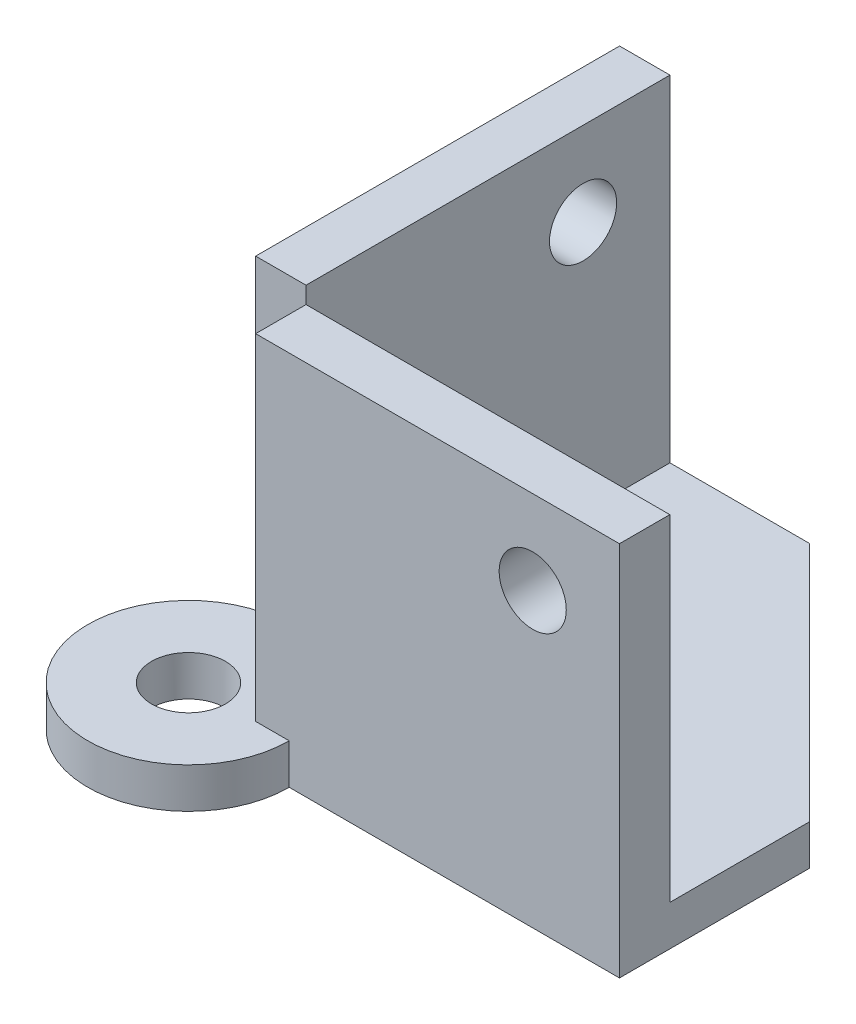
SolidWorks part; units mm, degrees
ref_plane "前视" through (0, 0, 0) normal (0, 0, 1) x (1, 0, 0)
ref_plane "上视" through (0, 0, 0) normal (0, 1, 0) x (1, 0, 0)
ref_plane "右视" through (0, 0, 0) normal (1, 0, 0) x (0, 0, -1)
sketch "Sketch1" plane through (0, 0, 0) normal (0, 1, 0) x (1, 0, 0)
  line L0 (0, 0) -> (0, 19)
  line L1 (0, 0) -> (19, 0)
  line L2 (19, 0) -> (0, 19)
  dimension "D1" = 19
  dimension "D2" = 19
extrude "Boss-Extrude1" add sketch "Sketch1" along normal blind 5
sketch "Sketch2" plane through (0, 5, 0) normal (0, 1, 0) x (1, 0, 0)
  line L0 (0, 19) -> (0, 0)
  line L1 (0, 0) -> (19, 0)
  line L2 (19, 0) -> (16, 3)
  line L3 (19, 0) -> (0, 19) construction
  line L4 (16, 3) -> (3, 3)
  line L5 (3, 3) -> (3, 16)
  line L6 (3, 16) -> (0, 19)
  dimension "D1" = 3
  dimension "D2" = 3
extrude "Boss-Extrude2" add sketch "Sketch2" along normal blind 15
sketch "Sketch3" plane through (0, 0, 0) normal (0, 0, 1) x (1, 0, 0)
  line L0 (0, 20) -> (0, 0) construction
  line L1 (0, 0) -> (19, 0) construction
  circle A0 centre (11.5, 15) radius 2
  dimension "D1" = 11.5
  dimension "D2" = 15
extrude "Cut-Extrude1" cut sketch "Sketch3" against normal through all
sketch "Sketch4" plane through (0, 0, 0) normal (-1, 0, 0) x (0, 0, 1)
  line L0 (-19, 0) -> (0, 0) construction
  line L1 (0, 20) -> (0, 0) construction
  circle A0 centre (-11.5, 15) radius 2
  dimension "D1" = 15
  dimension "D2" = 11.5
extrude "Cut-Extrude2" cut sketch "Sketch4" against normal through all
fillet "Fillet1" radius 1 6 edges at (9.5, 20, -3) (3, 20, -9.5) (1.5, 20, -17.5) (17.5, 20, -1.5) (19, 10, 0) (0, 10, -19)
sketch "Sketch5" plane through (0, 0, 0) normal (0, -1, 0) x (1, 0, 0)
  line L0 (28, 9) -> (-9, 9)
  line L1 (-9, 9) -> (-9, -28)
  line L3 (1.7071, -17.2929) -> (17.2929, -1.7071)
  line L4 (16.5858, 0) -> (0, 0)
  line L5 (0, 0) -> (0, -16.5858)
  line L6 (-9, -28) -> (28, 9)
  line L7 (0, 0) -> (16.5858, 0) construction
  line L8 (0, -16.5858) -> (0, 0) construction
  arc A2 (17.2929, -1.7071) -> (16.5858, 0) centre (16.5858, -1) ccw
  arc A3 (0, -16.5858) -> (1.7071, -17.2929) centre (1, -16.5858) ccw
  dimension "D2" = 9
  dimension "D3" = 9
  dimension "D1" = 0
extrude "Boss-Extrude3" add sketch "Sketch5" along normal blind 2.4
sketch "Sketch6" plane through (0, 0, 0) normal (0, 1, 0) x (1, 0, 0)
  line L0 (-9, -9) -> (-9, 28) construction
  line L1 (28, -9) -> (-9, -9) construction
  line L2 (-9, -9) -> (-9, 16.6732)
  line L3 (16.6669, -6) -> (16.6669, -9)
  line L4 (-6, 16.6732) -> (-9, 16.6732)
  line L5 (28, -6) -> (-6, -6)
  line L6 (-6, -6) -> (-6, 28)
  line L7 (16.6669, -6) -> (-6, -6)
  line L8 (-6, -6) -> (-6, 16.6732)
  line L9 (16.6669, -9) -> (-9, -9)
  dimension "D1" = 3
extrude "Boss-Extrude4" add sketch "Sketch6" along normal blind 20
sketch "Sketch7" plane through (0, 0, 9) normal (0, 0, 1) x (1, 0, 0)
  circle A0 centre (11.5, 15) radius 2 construction
  circle A1 centre (11.5, 15) radius 2
extrude "Cut-Extrude3" cut sketch "Sketch7" against normal through all both and the other way through all
sketch "Sketch8" plane through (-9, 0, 0) normal (-1, 0, 0) x (0, 0, 1)
  circle A0 centre (-11.5, 15) radius 2 construction
  circle A1 centre (-11.5, 15) radius 2
extrude "Cut-Extrude4" cut sketch "Sketch8" against normal through all both and the other way through all
sketch "Sketch9" plane through (0, 0, 0) normal (0, 1, 0) x (1, 0, 0)
  line L0 (16.6669, -9) -> (16.6669, -6) construction
  line L1 (-6, 16.6732) -> (-9, 16.6732) construction
  line L2 (-9, 16.6732) -> (-9, 28) construction
  line L3 (-9, 28) -> (1.7071, 17.2929) construction
  line L4 (28, -9) -> (16.6669, -9) construction
  line L5 (17.2929, 1.7071) -> (28, -9) construction
  line L6 (16.6669, -9) -> (16.6669, 2.3331)
  line L7 (2.3268, 16.6732) -> (-9, 16.6732)
  line L8 (-9, 16.6732) -> (-9, 28)
  line L9 (-9, 28) -> (17.2929, 1.7071)
  line L10 (28, -9) -> (16.6669, -9)
  line L11 (17.2929, 1.7071) -> (28, -9)
  line M2 (16.6669, -6) -> (16.6669, -9)
  line M3 (16.6669, -9) -> (28, -9)
  line M4 (28, -9) -> (17.2929, 1.7071)
  arc M5 (17.2929, 1.7071) -> (16.5858, 0) centre (16.5858, 1) cw
  arc M8 (0, 16.5858) -> (1.7071, 17.2929) centre (1, 16.5858) cw
  line M9 (1.7071, 17.2929) -> (-9, 28)
  line M10 (-9, 28) -> (-9, 16.6732)
  line M11 (-9, 16.6732) -> (-6, 16.6732)
extrude "Cut-Extrude5" cut sketch "Sketch9" against normal blind 20 contours L6 M2 M3 M4 M5 | L7 M8 M9 M10 M11
sketch "Sketch10" plane through (0, 0, 0) normal (0, 1, 0) x (1, 0, 0)
  line L2 (1.7071, 17.2929) -> (17.2929, 1.7071) construction
  line L3 (0, 16.5858) -> (0, 0) construction
  line L4 (0, 0) -> (16.5858, 0) construction
  line L5 (1.7071, 17.2929) -> (17.2929, 1.7071)
  line L6 (0, 16.5858) -> (0, 0)
  line L7 (0, 0) -> (16.5858, 0)
  arc A2 (1.7071, 17.2929) -> (0.0038, 16.6732) centre (1, 16.5858) ccw construction
  arc A3 (16.6669, 0.0033) -> (17.2929, 1.7071) centre (16.5858, 1) ccw construction
  arc A4 (1.7071, 17.2929) -> (0, 16.5858) centre (1, 16.5858) ccw
  arc A5 (16.5858, 0) -> (17.2929, 1.7071) centre (16.5858, 1) ccw
extrude "Cut-Extrude6" cut sketch "Sketch10" along normal through all
sketch "Sketch11" plane through (0, 0, 0) normal (0, 1, 0) x (1, 0, 0)
  line L0 (0.0038, 16.6732) -> (-6, 16.6732) construction
  line L1 (17.2929, 1.7071) -> (1.7071, 17.2929) construction
  line L2 (16.6669, -9) -> (16.6669, 0.0033) construction
  line L3 (2.3268, 16.6732) -> (0.0038, 16.6732)
  line L4 (17.2929, 1.7071) -> (16.6669, 2.3331)
  line L5 (16.6669, 0.0033) -> (16.6669, 2.3331)
  line L6 (2.3268, 16.6732) -> (1.7071, 17.2929)
  arc A0 (1.7071, 17.2929) -> (0.0038, 16.6732) centre (1, 16.5858) ccw construction
  arc A1 (16.6669, 0.0033) -> (17.2929, 1.7071) centre (16.5858, 1) ccw construction
  arc A2 (1.7071, 17.2929) -> (0.0038, 16.6732) centre (1, 16.5858) ccw
  arc A3 (16.6669, 0.0033) -> (17.2929, 1.7071) centre (16.5858, 1) ccw
extrude "Cut-Extrude7" cut sketch "Sketch11" against normal through all
sketch "Sketch12" plane through (0, -2.4, 0) normal (0, -1, 0) x (1, 0, 0)
  circle A0 centre (-9, 9) radius 6
extrude "Boss-Extrude5" add sketch "Sketch12" against normal blind 2.4
sketch "Sketch13" plane through (0, 0, 0) normal (0, 1, 0) x (1, 0, 0)
  circle A0 centre (-9, -9) radius 2.2
extrude "Cut-Extrude8" cut sketch "Sketch13" against normal through all both and the other way through all
sketch "Sketch14" plane through (0, 0, 0) normal (0, 1, 0) x (1, 0, 0)
  circle A1 centre (-9, -9) radius 4
extrude "Cut-Extrude9" cut sketch "Sketch14" along normal through all
sketch "Sketch15" plane through (0, 0, 0) normal (0, 1, 0) x (1, 0, 0)
  line L0 (-9, -5) -> (-5, -5)
  line L1 (-5, -9) -> (-5, -5)
  arc A0 (-5, -9) -> (-9, -5) centre (-9, -9) ccw construction
  arc A1 (-5, -9) -> (-9, -5) centre (-9, -9) ccw
extrude "Cut-Extrude10" cut sketch "Sketch15" along normal through all
